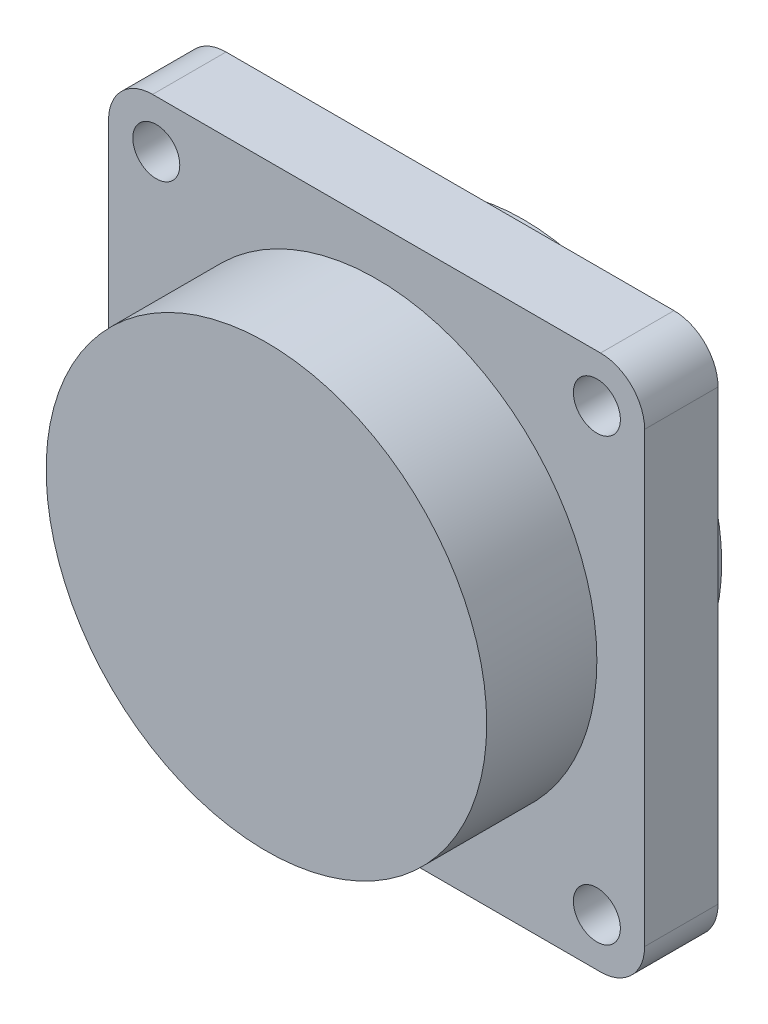
SolidWorks part; units mm, degrees
ref_plane "前视基准面" through (0, 0, 0) normal (0, 0, 1) x (1, 0, 0)
ref_plane "上视基准面" through (0, 0, 0) normal (0, 1, 0) x (1, 0, 0)
ref_plane "右视基准面" through (0, 0, 0) normal (1, 0, 0) x (0, 0, -1)
sketch "草图1" plane through (0, 0, 0) normal (0, 0, 1) x (1, 0, 0)
  line L0 (0, 0) -> (0, 46.7107) construction
  line L1 (-18.25, 18.25) -> (18.25, 18.25)
  line L2 (-18.25, 18.25) -> (-18.25, -18.25)
  line L3 (-18.25, -18.25) -> (18.25, -18.25)
  line L4 (18.25, 18.25) -> (18.25, -18.25)
  line L5 (0, 0) -> (59.3509, 0) construction
  dimension "D1" = 36.5
  dimension "D2" = 36.5
extrude "凸台-拉伸1" add sketch "草图1" along normal blind 5
sketch "草图2" plane through (0, 0, 5) normal (0, 0, 1) x (1, 0, 0)
  circle A0 centre (0, 0) radius 15
  dimension "D1" = 30
extrude "凸台-拉伸2" add sketch "草图2" along normal blind 7.5
sketch "草图3" plane through (0, 0, 0) normal (0, 0, -1) x (-1, 0, 0)
  circle A0 centre (0, 0) radius 13.5
  dimension "D1" = 27
extrude "凸台-拉伸3" add sketch "草图3" along normal blind 5
sketch "草图4" plane through (0, 0, 0) normal (0, 0, -1) x (-1, 0, 0)
  line L0 (0, 0) -> (0, 24.2555) construction
  line L1 (0, 0) -> (-29.459, 0) construction
  circle A0 centre (-15, 15) radius 1.6
  circle A1 centre (-15, -15) radius 1.6
  circle A2 centre (15, -15) radius 1.6
  circle A3 centre (15, 15) radius 1.6
  dimension "D3" = 3.2
  dimension "D1" = 30
  dimension "D2" = 30
extrude "切除-拉伸1" cut sketch "草图4" against normal through all
fillet "圆角1" radius 3 4 edges at (-18.25, -18.25, 2.5) (18.25, -18.25, 2.5) (-18.25, 18.25, 2.5) (18.25, 18.25, 2.5)
